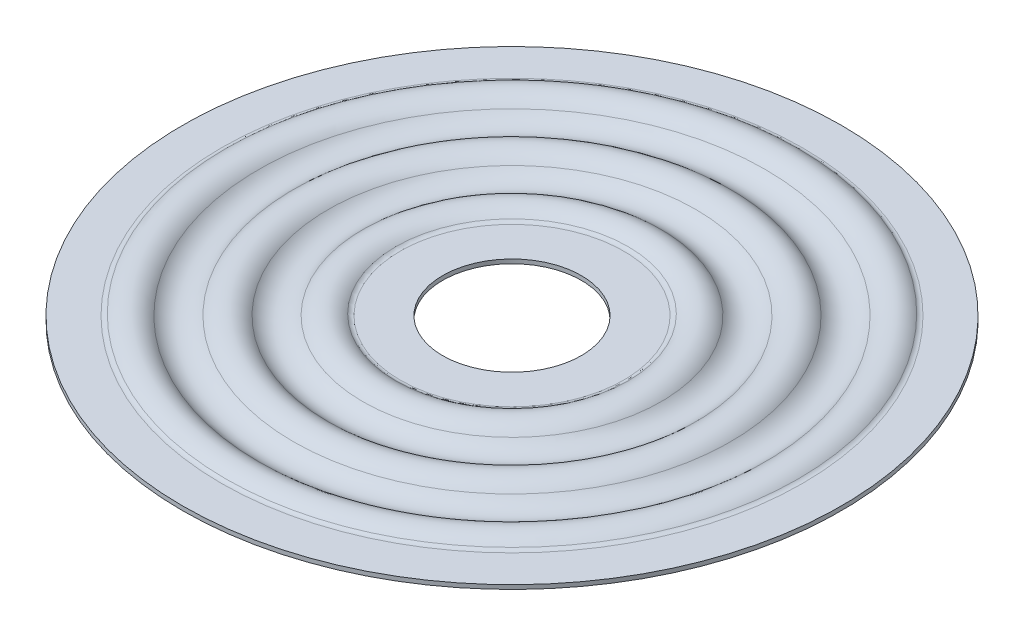
SolidWorks part; units mm, degrees
ref_plane "Спереди" through (0, 0, 0) normal (0, 0, 1) x (1, 0, 0)
ref_plane "Сверху" through (0, 0, 0) normal (0, 1, 0) x (1, 0, 0)
ref_plane "Справа" through (0, 0, 0) normal (1, 0, 0) x (0, 0, -1)
sketch "Эскиз1" plane through (0, 0, 0) normal (0, 0, 1) x (1, 0, 0)
  line L0 (-10, 0) -> (-47.5, 0)
  line L1 (-47.5, 0) -> (-47.5, 10)
  line L2 (-47.5, 10) -> (-41.5, 10)
  line L3 (-16.5, 10) -> (-10, 10)
  line L4 (-10, 10) -> (-10, 0)
  line L5 (-10, 0) -> (0, 0) construction
  line L6 (-10, 10) -> (0, 10) construction
  line L7 (0, 10) -> (0, 0) construction
  arc A0 (-41.5, 10) -> (-36.5, 10) centre (-39, 7.5505) cw
  arc A1 (-36.5, 10) -> (-31.5, 10) centre (-34, 12.4495) ccw
  arc A2 (-31.5, 10) -> (-26.5, 10) centre (-29, 7.5505) cw
  arc A3 (-26.5, 10) -> (-21.5, 10) centre (-24, 12.4495) ccw
  arc A4 (-21.5, 10) -> (-16.5, 10) centre (-19, 7.5505) cw
  dimension "D6" = 3.5
  dimension "D1" = 5
  dimension "D2" = 10
  dimension "D3" = 47.5
  dimension "D4" = 6
  dimension "D5" = 10
revolve "Повернуть1" add sketch "Эскиз1" angle 360 about L7
fillet "Скругление1" radius 1 2 edges at (0, 10, 16.5) (0, 10, 41.5)
shell "Оболочка1" thickness 0.6
